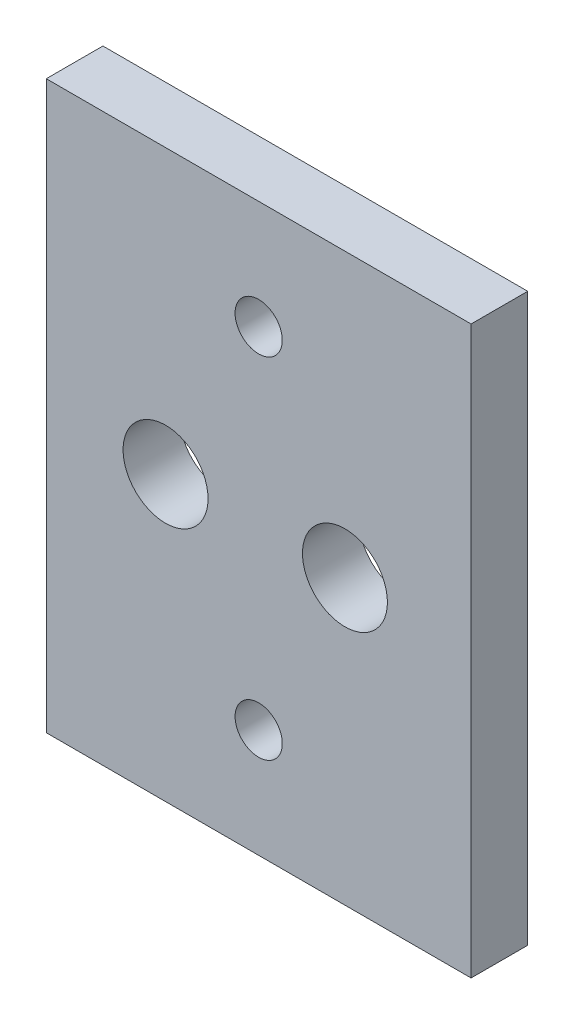
SolidWorks part; units mm, degrees
material "PE High Density"
ref_plane "Front Plane" through (0, 0, 0) normal (0, 0, 1) x (1, 0, 0)
ref_plane "Top Plane" through (0, 0, 0) normal (0, 1, 0) x (1, 0, 0)
ref_plane "Right Plane" through (0, 0, 0) normal (1, 0, 0) x (0, 0, -1)
ref_plane "Plane1" through (0, 0, 0) normal (0, 0, -1) x (-1, 0, 0)
sketch "Sketch1" plane through (0, 0, 0) normal (0, 0, -1) x (-1, 0, 0)
  line L0 (-22.5, 30) -> (-22.5, -30)
  line L1 (-22.5, -30) -> (22.5, -30)
  line L2 (22.5, -30) -> (22.5, 30)
  line L3 (22.5, 30) -> (-22.5, 30)
  circle A0 centre (-9.1371, 0.034) radius 4.5
  circle A1 centre (0, 18.5) radius 2.5
  circle A2 centre (0, -18.5) radius 2.5
  circle A3 centre (9.8629, 0.034) radius 4.5
  dimension "D1" = 11.5
  dimension "D4" = 5
  dimension "D5" = 11.5
  dimension "D6" = 5
  dimension "D2" = 45
  dimension "D3" = 60
extrude "Boss-Extrude1" add sketch "Sketch1" against normal blind 6
